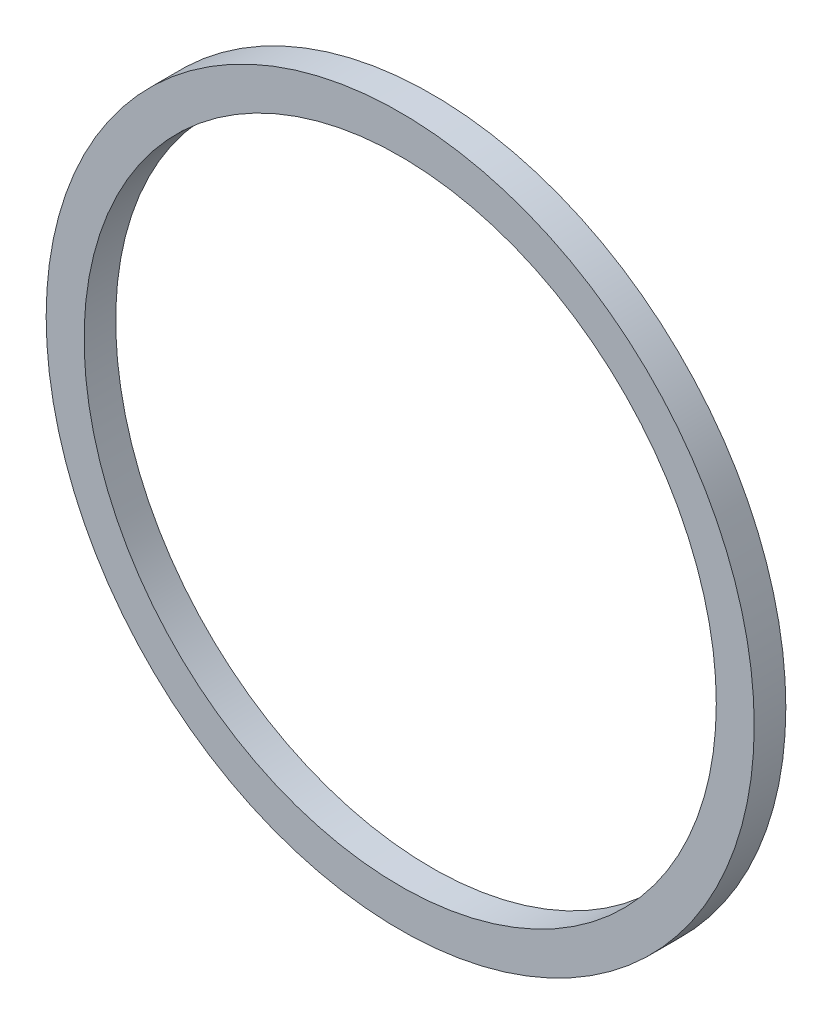
SolidWorks part; units mm, degrees
ref_plane "前视基准面" through (0, 0, 0) normal (0, 0, 1) x (1, 0, 0)
ref_plane "上视基准面" through (0, 0, 0) normal (0, 1, 0) x (1, 0, 0)
ref_plane "右视基准面" through (0, 0, 0) normal (1, 0, 0) x (0, 0, -1)
sketch "草图1" plane through (0, 0, 0) normal (0, 0, 1) x (1, 0, 0)
  circle A0 centre (0, 0) radius 11.2
  circle A1 centre (0, 0) radius 10
  dimension "D1" = 20
  dimension "D2" = 22.4
extrude "凸台-拉伸1" add sketch "草图1" along normal blind 1 contours A0
